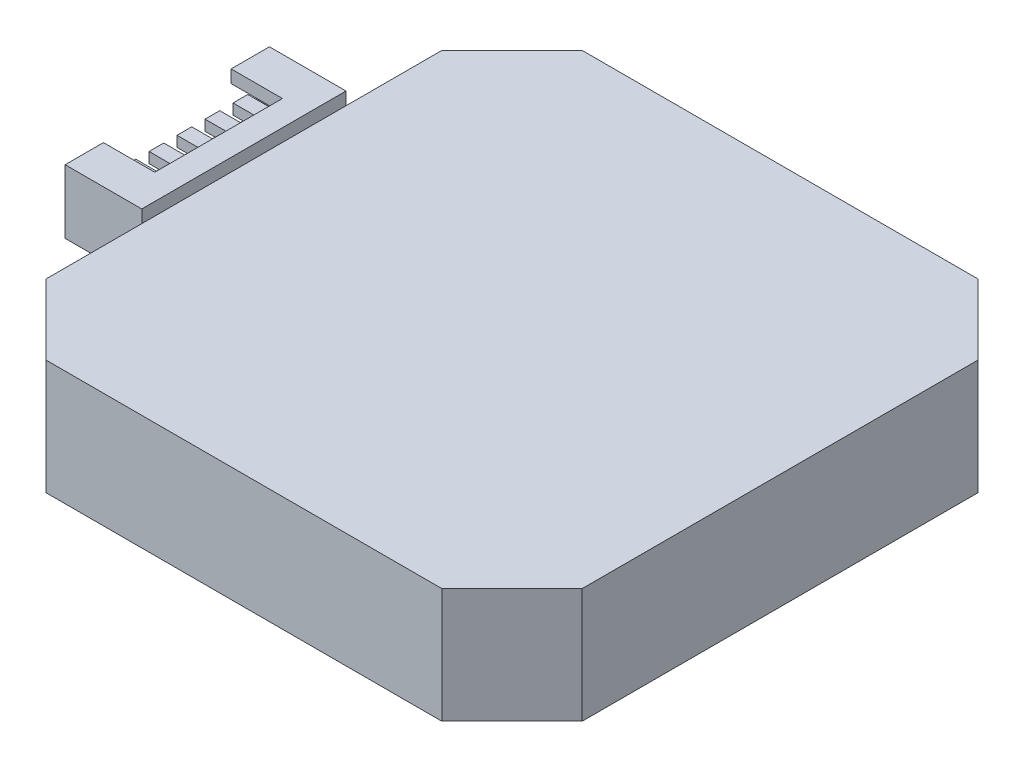
SolidWorks part; units mm, degrees
ref_plane "Front Plane" through (0, 0, 0) normal (0, 0, 1) x (1, 0, 0)
ref_plane "Top Plane" through (0, 0, 0) normal (0, 1, 0) x (1, 0, 0)
ref_plane "Right Plane" through (0, 0, 0) normal (1, 0, 0) x (0, 0, -1)
sketch "Sketch1" plane through (0, 0, 0) normal (0, 1, 0) x (1, 0, 0)
  line L1 (-21, 21) -> (21, 21)
  line L2 (-21, 21) -> (-21, -21)
  line L3 (-21, -21) -> (21, -21)
  line L4 (21, 21) -> (21, -21)
  line L5 (-21, 21) -> (21, -21) construction
  line L6 (-21, -21) -> (21, 21) construction
  point P0 (0, 0)
  dimension "D1" = 42
  dimension "D2" = 42
extrude "Nema 17" add sketch "Sketch1" along normal blind 9
chamfer "Chamfer1" distance 5.5 angle 45 4 edges at (-21, 4.5, -21) (21, 4.5, -21) (21, 4.5, 21) (-21, 4.5, 21)
sketch "Sketch2" plane through (0, 0, 0) normal (0, -1, 0) x (1, 0, 0)
  line L0 (-21, -15.5) -> (-21, 15.5) construction
  line L1 (15.5, -21) -> (-15.5, -21) construction
  line L2 (0, 0) -> (0, 21) construction
  line L4 (0, 0) -> (21, 0) construction
  circle A0 centre (-15.5, -15.5) radius 3
  circle A1 centre (15.5, -15.5) radius 3
  circle A2 centre (-15.5, 15.5) radius 3
  circle A3 centre (15.5, 15.5) radius 3
  dimension "D1" = 5.5
  dimension "D2" = 6
  dimension "D3" = 5.5
extrude "M6 Bolt Holes" cut sketch "Sketch2" against normal blind 8
sketch "Sketch3" plane through (-21, 0, 0) normal (-1, 0, 0) x (0, 0, 1)
  line L0 (-8, 3) -> (8, 3)
  line L1 (-8, 3) -> (-8, 0)
  line L2 (8, 3) -> (8, 0)
  line L3 (-8, 0) -> (8, 0)
  line L4 (-8, 3) -> (8, 0) construction
  line L5 (8, 3) -> (-8, 0) construction
  line L6 (-15.5, 0) -> (15.5, 0) construction
  line L9 (15.5, 0) -> (15.5, 9) construction
  point P1 (0, 1.5)
  point P3 (8, 1.5)
  dimension "D1" = 3
  dimension "D2" = 16
  dimension "D3" = 7.5
extrude "Boss-Extrude1" add sketch "Sketch3" along normal blind 4
sketch "Sketch5" plane through (-21, 0, 0) normal (-1, 0, 0) x (0, 0, 1)
  line L0 (-8, 5) -> (8, 5)
  line L1 (-8, 5) -> (-8, 10)
  line L2 (8, 5) -> (8, 10)
  line L3 (-8, 10) -> (8, 10)
  line L5 (-8, 0) -> (8, 0) construction
  dimension "D1" = 5
  dimension "D2" = 5
extrude "Boss-Extrude2" add sketch "Sketch5" along normal blind 6
sketch "Sketch6" plane through (-27, 0, 0) normal (-1, 0, 0) x (0, 0, 1)
  line L0 (-8, 9) -> (-8, 5) construction
  line L1 (-7, 9) -> (7, 9)
  line L2 (-7, 9) -> (-7, 6)
  line L3 (-7, 6) -> (7, 6)
  line L4 (7, 9) -> (7, 6)
  line L5 (8, 5) -> (8, 10) construction
  line L6 (8, 10) -> (-8, 10) construction
  line L7 (-8, 5) -> (8, 5) construction
  dimension "D1" = 1
  dimension "D2" = 1
  dimension "D3" = 1
  dimension "D4" = 1
extrude "Cut-Extrude1" cut sketch "Sketch6" against normal blind 5
sketch "Sketch7" plane through (0, 10, 0) normal (0, 1, 0) x (1, 0, 0)
  line L0 (-27, 5) -> (-27, -5)
  line L1 (-27, 5) -> (-22.9806, 5)
  line L2 (-27, -5) -> (-22.9806, -5)
  line L3 (-22.9806, 5) -> (-22.9806, -5)
  line L4 (-27, -8) -> (-27, 8) construction
  line L5 (-27, 8) -> (-21, 8) construction
  line L6 (-27, -8) -> (-21, -8) construction
  dimension "D1" = 3
  dimension "D2" = 3
extrude "Cut-Extrude2" cut sketch "Sketch7" against normal blind 1
sketch "Sketch8" plane through (-22, 0, 0) normal (-1, 0, 0) x (0, 0, 1)
  line L1 (4.9642, 7.9136) -> (6.1144, 7.9136)
  line L2 (4.9642, 7.9136) -> (4.9642, 7.085)
  line L3 (4.9642, 7.085) -> (6.1144, 7.085)
  line L4 (6.1144, 7.9136) -> (6.1144, 7.085)
  line L6 (-7, 6) -> (7, 6) construction
  line L8 (2.7714, 7.9136) -> (2.7714, 7.085)
  line L9 (2.7714, 7.9136) -> (3.9216, 7.9136)
  line L10 (3.9216, 7.9136) -> (3.9216, 7.085)
  line L11 (2.7714, 7.085) -> (3.9216, 7.085)
  line L12 (0.5785, 7.9136) -> (0.5785, 7.085)
  line L13 (0.5785, 7.9136) -> (1.7288, 7.9136)
  line L14 (1.7288, 7.9136) -> (1.7288, 7.085)
  line L15 (0.5785, 7.085) -> (1.7288, 7.085)
  line L16 (-1.6143, 7.9136) -> (-1.6143, 7.085)
  line L17 (-1.6143, 7.9136) -> (-0.4641, 7.9136)
  line L18 (-0.4641, 7.9136) -> (-0.4641, 7.085)
  line L19 (-1.6143, 7.085) -> (-0.4641, 7.085)
  line L20 (-3.8072, 7.9136) -> (-3.8072, 7.085)
  line L21 (-3.8072, 7.9136) -> (-2.6569, 7.9136)
  line L22 (-2.6569, 7.9136) -> (-2.6569, 7.085)
  line L23 (-3.8072, 7.085) -> (-2.6569, 7.085)
  line L24 (-6, 7.9136) -> (-6, 7.085)
  line L25 (-6, 7.9136) -> (-4.8498, 7.9136)
  line L26 (-4.8498, 7.9136) -> (-4.8498, 7.085)
  line L27 (-6, 7.085) -> (-4.8498, 7.085)
  line L28 (-7, 9) -> (-7, 6) construction
  dimension "D1" = 1.085
  dimension "D2" = 6
  dimension "D3" = 1
extrude "Boss-Extrude3" add sketch "Sketch8" along normal blind 5
chamfer "Chamfer2" distance 0.3 angle 45 24 edges at (-27, 7.9136, 5.5393) (-27, 7.4993, 6.1144) (-27, 7.085, 5.5393) (-27, 7.4993, 4.9642) (-27, 7.4993, 3.9216) (-27, 7.085, 3.3465) (-27, 7.4993, 2.7714) (-27, 7.9136, 3.3465) (-27, 7.4993, 1.7288) (-27, 7.085, 1.1536) (-27, 7.4993, 0.5785) (-27, 7.9136, 1.1536) (-27, 7.4993, -0.4641) (-27, 7.085, -1.0392) (-27, 7.4993, -1.6143) (-27, 7.9136, -1.0392) (-27, 7.4993, -2.6569) (-27, 7.085, -3.232) (-27, 7.4993, -3.8072) (-27, 7.9136, -3.232) (-27, 7.4993, -4.8498) (-27, 7.085, -5.4249) (-27, 7.4993, -6) (-27, 7.9136, -5.4249)
